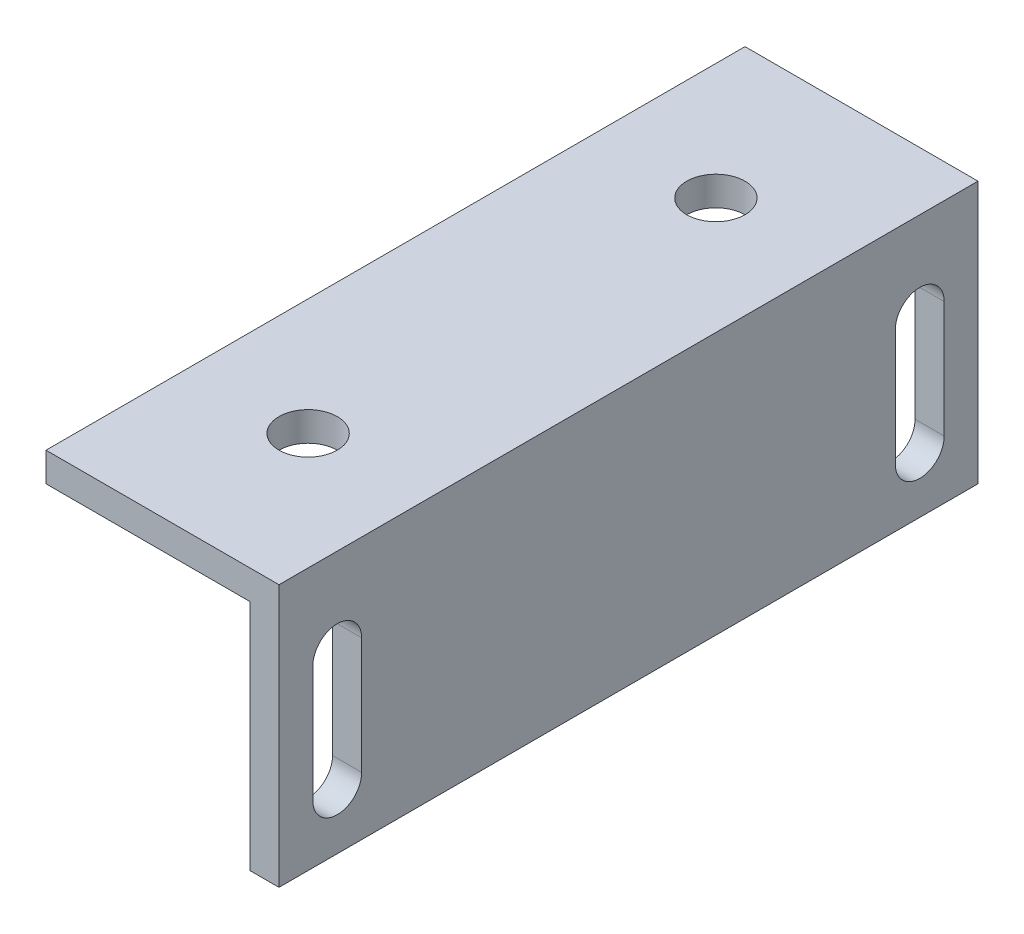
SolidWorks part; units mm, degrees
ref_plane "Front Plane" through (0, 0, 0) normal (0, 0, 1) x (1, 0, 0)
ref_plane "Top Plane" through (0, 0, 0) normal (0, 1, 0) x (1, 0, 0)
ref_plane "Right Plane" through (0, 0, 0) normal (1, 0, 0) x (0, 0, -1)
sketch "Sketch1" plane through (0, 0, 0) normal (0, 0, 1) x (1, 0, 0)
  line L0 (0, -50.8) -> (0, 0)
  line L1 (0, 0) -> (-25.4, 0)
  line L2 (-3.175, -50.8) -> (-3.175, -3.175)
  line L3 (-3.175, -3.175) -> (-25.4, -3.175)
  line L4 (-25.4, 0) -> (-25.4, -3.175)
  line L5 (0, -50.8) -> (-3.175, -50.8)
  dimension "D1" = 25.4
  dimension "D2" = 50.8
  dimension "D3" = 3.175
extrude "Boss-Extrude1" add sketch "Sketch1" along normal blind 76.2
sketch "Sketch2" plane through (0, 0, 0) normal (0, 1, 0) x (1, 0, 0)
  line L0 (0, -38.1) -> (-25.4, -38.1) construction
  line L1 (0, -76.2) -> (0, 0) construction
  line L2 (-25.4, -76.2) -> (-25.4, 0) construction
  line L3 (-12.7, -38.1) -> (-12.7, -15.875) construction
  line L4 (-12.7, -38.1) -> (-12.7, -60.325) construction
  circle A0 centre (-12.7, -15.875) radius 3.175
  circle A1 centre (-12.7, -60.325) radius 3.175
  dimension "D1" = 6.35
  dimension "D2" = 44.45
extrude "Cut-Extrude1" cut sketch "Sketch2" against normal up to next
sketch "Sketch3" plane through (0, 0, 76.2) normal (0, 0, 1) x (1, 0, 0)
  line L0 (-3.175, -3.175) -> (-3.175, -50.8) construction
  line L1 (0, -50.8) -> (-3.175, -50.8)
  line L2 (0, -50.8) -> (0, -28.575)
  line L3 (0, -28.575) -> (-3.175, -28.575)
  line L4 (-3.175, -50.8) -> (-3.175, -28.575)
  line L5 (0, -50.8) -> (-3.175, -28.575) construction
  line L6 (0, -28.575) -> (-3.175, -50.8) construction
  line L7 (-25.4, -3.175) -> (-3.175, -3.175) construction
  point P4 (-1.5875, -39.6875)
  point P8 (-1.5875, -28.575)
  dimension "D1" = 25.4
extrude "Cut-Extrude2" cut sketch "Sketch3" against normal up to next
sketch "Sketch4" plane through (-3.175, 0, 0) normal (-1, 0, 0) x (0, 0, 1)
  line L0 (69.85, -9.525) -> (69.85, -22.225) construction
  line L1 (72.515, -9.525) -> (72.515, -22.225)
  line L2 (67.185, -9.525) -> (67.185, -22.225)
  line L3 (0, -28.575) -> (76.2, -28.575) construction
  line L4 (76.2, -3.175) -> (0, -3.175) construction
  line L5 (76.2, -3.175) -> (76.2, -28.575) construction
  line L6 (38.1, -3.175) -> (38.1, -28.575) construction
  line L7 (6.35, -9.525) -> (6.35, -22.225) construction
  line L8 (3.685, -9.525) -> (3.685, -22.225)
  line L9 (9.015, -9.525) -> (9.015, -22.225)
  arc A0 (72.515, -9.525) -> (67.185, -9.525) centre (69.85, -9.525) ccw
  arc A1 (67.185, -22.225) -> (72.515, -22.225) centre (69.85, -22.225) ccw
  arc A2 (3.685, -9.525) -> (9.015, -9.525) centre (6.35, -9.525) cw
  arc A3 (9.015, -22.225) -> (3.685, -22.225) centre (6.35, -22.225) cw
  point P2 (69.85, -15.875)
  point P17 (6.35, -15.875)
  dimension "D3" = 6.35
  dimension "D1" = 5.33
  dimension "D2" = 6.35
  dimension "D4" = 6.35
extrude "Cut-Extrude3" cut sketch "Sketch4" against normal up to next
